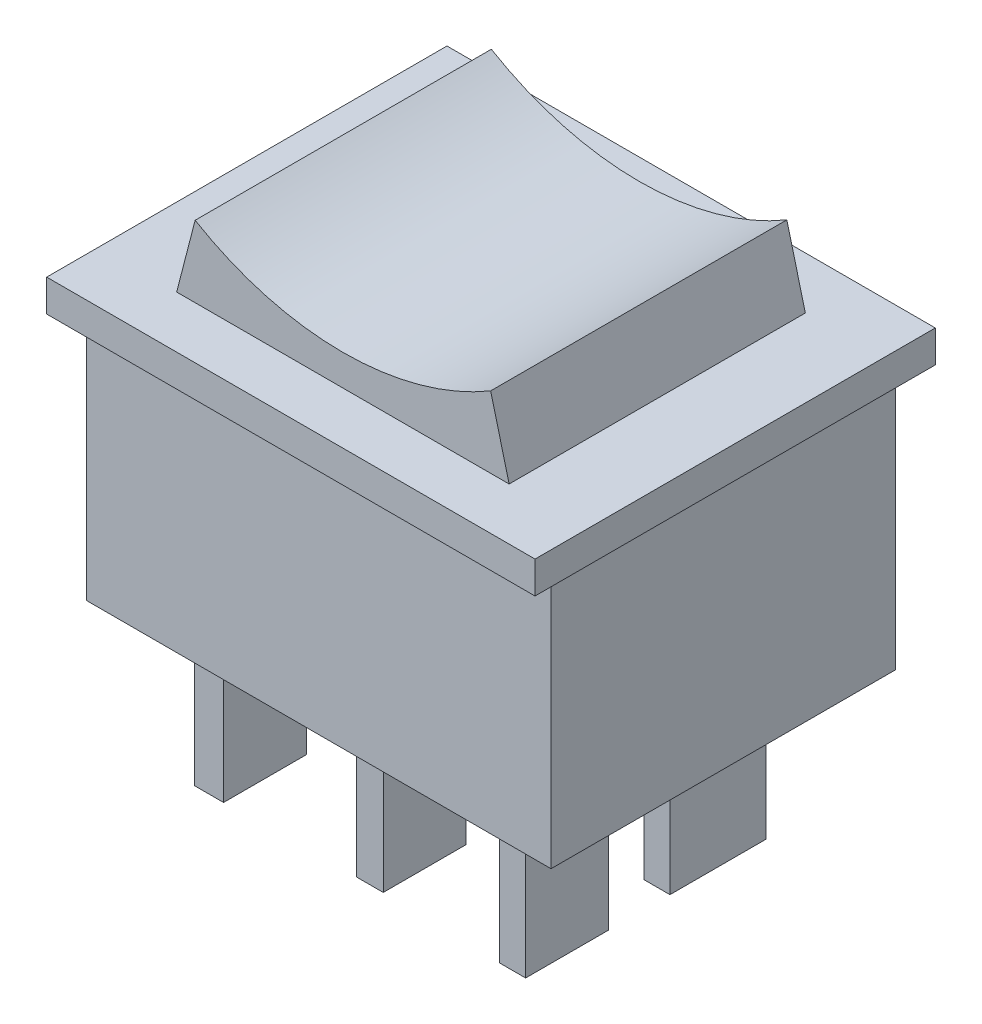
SolidWorks part; units mm, degrees
ref_plane "前视基准面" through (0, 0, 0) normal (0, 0, 1) x (1, 0, 0)
ref_plane "上视基准面" through (0, 0, 0) normal (0, 1, 0) x (1, 0, 0)
ref_plane "右视基准面" through (0, 0, 0) normal (1, 0, 0) x (0, 0, -1)
sketch "草图1" plane through (0, 0, 0) normal (0, 1, 0) x (1, 0, 0)
  line L1 (-15.25, -12.5) -> (15.25, -12.5)
  line L2 (-15.25, -12.5) -> (-15.25, 12.5)
  line L3 (-15.25, 12.5) -> (15.25, 12.5)
  line L4 (15.25, -12.5) -> (15.25, 12.5)
  line L5 (-15.25, -12.5) -> (15.25, 12.5) construction
  line L6 (-15.25, 12.5) -> (15.25, -12.5) construction
  point P0 (0, 0)
  dimension "D1" = 30.5
  dimension "D2" = 25
extrude "凸台-拉伸1" add sketch "草图1" along normal blind 2
sketch "草图2" plane through (0, 0, 0) normal (0, -1, 0) x (1, 0, 0)
  line L1 (-14.5, -10.75) -> (14.5, -10.75)
  line L2 (-14.5, -10.75) -> (-14.5, 10.75)
  line L3 (-14.5, 10.75) -> (14.5, 10.75)
  line L4 (14.5, -10.75) -> (14.5, 10.75)
  line L5 (-14.5, -10.75) -> (14.5, 10.75) construction
  line L6 (-14.5, 10.75) -> (14.5, -10.75) construction
  point P0 (0, 0)
  dimension "D1" = 29
  dimension "D2" = 21.5
extrude "凸台-拉伸2" add sketch "草图2" along normal blind 16
sketch "草图3" plane through (0, -16, 0) normal (0, -1, 0) x (1, 0, 0)
  line L1 (-10.7117, 7.7945) -> (-8.9091, 7.7945)
  line L2 (-10.7117, 7.7945) -> (-10.7117, 2.6271)
  line L3 (-10.7117, 2.6271) -> (-8.9091, 2.6271)
  line L4 (-8.9091, 7.7945) -> (-8.9091, 2.6271)
  line L5 (-10.7117, -1.2183) -> (-8.9091, -1.2183)
  line L6 (-10.7117, -1.2183) -> (-10.7117, -7.2269)
  line L7 (-10.7117, -7.2269) -> (-8.9091, -7.2269)
  line L8 (-8.9091, -1.2183) -> (-8.9091, -7.2269)
  line L9 (-0.7375, 7.6743) -> (0.9449, 7.6743)
  line L10 (-0.7375, 7.6743) -> (-0.7375, 2.507)
  line L11 (-0.7375, 2.507) -> (0.9449, 2.507)
  line L12 (0.9449, 7.6743) -> (0.9449, 2.507)
  line L13 (-0.7375, -1.3385) -> (0.9449, -1.3385)
  line L14 (-0.7375, -1.3385) -> (-0.7375, -7.3471)
  line L15 (-0.7375, -7.3471) -> (0.9449, -7.3471)
  line L16 (0.9449, -1.3385) -> (0.9449, -7.3471)
  line L17 (8.3955, 7.8546) -> (10.0178, 7.8546)
  line L18 (8.3955, 7.8546) -> (8.3955, 2.6872)
  line L19 (8.3955, 2.6872) -> (10.0178, 2.6872)
  line L20 (10.0178, 7.8546) -> (10.0178, 2.6872)
  line L21 (8.3955, -1.1582) -> (10.0178, -1.1582)
  line L22 (8.3955, -1.1582) -> (8.3955, -7.1668)
  line L23 (8.3955, -7.1668) -> (10.0178, -7.1668)
  line L24 (10.0178, -1.1582) -> (10.0178, -7.1668)
extrude "凸台-拉伸3" add sketch "草图3" along normal blind 9.6
sketch "草图4" plane through (0, 0, 0) normal (0, 0, 1) x (1, 0, 0)
  line L0 (0, 2) -> (0, 5.856) construction
  line L1 (-15.25, 2) -> (15.25, 2) construction
  line L2 (10.3826, 2) -> (-10.3826, 2)
  line L3 (-10.3826, 2) -> (-9.2282, 6.4606)
  line L4 (10.3826, 2) -> (9.2282, 6.4606)
  arc A0 (-9.2282, 6.4606) -> (0, 3.928) centre (0, 22.0071) ccw
  arc A1 (9.2282, 6.4606) -> (0, 3.928) centre (0, 22.0071) cw
extrude "凸台-拉伸4" add sketch "草图4" along normal mid plane 18.5
